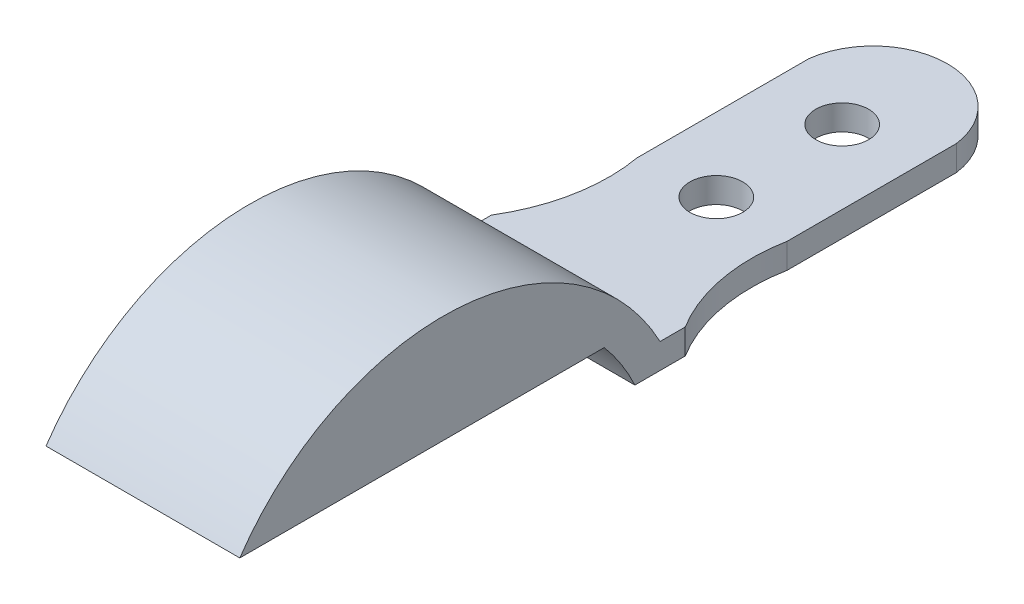
SolidWorks part; units mm, degrees
ref_plane "Front Plane" through (0, 0, 0) normal (0, 0, 1) x (1, 0, 0)
ref_plane "Top Plane" through (0, 0, 0) normal (0, 1, 0) x (1, 0, 0)
ref_plane "Right Plane" through (0, 0, 0) normal (1, 0, 0) x (0, 0, -1)
sketch "Sketch1" plane through (0, 0, 0) normal (0, 1, 0) x (1, 0, 0)
  line L0 (-9.779, -12.9185) -> (9.779, -12.9185)
  line L1 (-7.4314, -0.571) -> (-7.4314, 16.7965)
  line L2 (7.4314, -0.2922) -> (7.4314, 16.7965)
  circle A0 centre (0, 0) radius 2.667
  circle A5 centre (0, 12.7) radius 2.667
  arc A6 (-7.4314, 16.7965) -> (7.4314, 16.7965) centre (0, 15.8224) cw
  arc A9 (-7.4314, -0.571) -> (-9.779, -12.9185) centre (-24.9448, -3.6381) cw
  arc A10 (7.4314, -0.2922) -> (9.779, -12.9185) centre (24.9058, -3.5745) ccw
  point P6 (0, -12.9185)
  point P14 (0, 23.3174)
  dimension "D1" = 5.334
  dimension "D2" = 12.3475
  dimension "D4" = 5.334
  dimension "D5" = 12.7
  dimension "D6" = 7.4949
  dimension "D10" = 28.7409
  dimension "D12" = 3.1224
  dimension ".7" = 17.78
  dimension "D7" = 19.558
  dimension "D8" = 7.4314
extrude "Boss-Extrude1" add sketch "Sketch1" along normal blind 2.54
sketch "Sketch2" plane through (0, 0, 0) normal (1, 0, 0) x (0, 0, -1)
  line L0 (-60.4165, 0) -> (-57.1145, 0)
  line L1 (-12.9185, 0) -> (-17.9985, 0)
  line L2 (-12.9185, 2.54) -> (-12.9185, 0)
  line L3 (-12.9185, 2.54) -> (-15.4585, 2.54)
  arc A3 (-57.1145, 0) -> (-17.9985, 0) centre (-37.5565, -9.144) cw
  arc A4 (-60.4165, 0) -> (-15.4585, 2.54) centre (-37.3521, -9.0902) cw
  dimension "D5" = 21.59
  dimension "D6" = 24.791
  dimension "D1" = 3.302
  dimension "D2" = 5.08
  dimension "D3" = 39.116
  dimension "D4" = 2.54
extrude "Boss-Extrude7" add sketch "Sketch2" along normal up to vertex (9.779 mm away) and the other way up to vertex (9.779 mm away) up to point (9.779, 2.54, 12.9185) other way up to point (-9.779, 2.54, 12.9185)
sketch "Sketch8" plane through (-9.779, 0, 0) normal (-1, 0, 0) x (0, 0, 1)
  line L0 (37.5565, 12.446) -> (37.5565, 4.826) construction
  line L1 (21.0954, 4.826) -> (54.0176, 4.826)
  arc A0 (57.1145, 0) -> (17.9985, 0) centre (37.5565, -9.144) ccw construction
  arc A1 (54.0176, 4.826) -> (21.0954, 4.826) centre (37.5565, -9.144) ccw
  dimension "D1" = 7.62
extrude "Boss-Extrude8" add sketch "Sketch8" against normal blind 3.175
sketch "Sketch9" plane through (9.779, 0, 0) normal (1, 0, 0) x (0, 0, -1)
  line L1 (-54.0176, 4.826) -> (-21.0954, 4.826)
  line L2 (-54.0176, 4.826) -> (-21.0954, 4.826)
  arc A1 (-21.0954, 4.826) -> (-54.0176, 4.826) centre (-37.5565, -9.144) ccw
  arc A2 (-21.0954, 4.826) -> (-54.0176, 4.826) centre (-37.5565, -9.144) ccw
  dimension "D1" = 0
extrude "Boss-Extrude9" add sketch "Sketch9" against normal blind 3.175
sketch "Sketch10" plane through (-9.779, 0, 0) normal (-1, 0, 0) x (0, 0, 1)
  line L0 (54.0176, 4.826) -> (57.8688, 4.826)
  line L5 (12.9185, 2.54) -> (12.9185, 0)
  line L6 (12.9185, 0) -> (17.9985, 0)
  line L7 (21.0954, 4.826) -> (54.0176, 4.826)
  line L8 (57.1145, 0) -> (60.4165, 0)
  line L9 (15.4585, 2.54) -> (12.9185, 2.54)
  line L13 (57.1145, 0) -> (60.4165, 0)
  arc A3 (21.0954, 4.826) -> (17.9985, 0) centre (37.5565, -9.144) ccw
  arc A4 (57.1145, 0) -> (54.0176, 4.826) centre (37.5565, -9.144) ccw
  arc A5 (60.4165, 0) -> (15.4585, 2.54) centre (37.3521, -9.0902) ccw
  arc A7 (57.1145, 0) -> (54.0176, 4.826) centre (37.5565, -9.144) ccw
  arc A8 (60.4165, 0) -> (57.8688, 4.826) centre (37.3521, -9.0902) ccw
  dimension "D1" = 0
extrude "Cut-Extrude1" cut sketch "Sketch10" against normal through all
